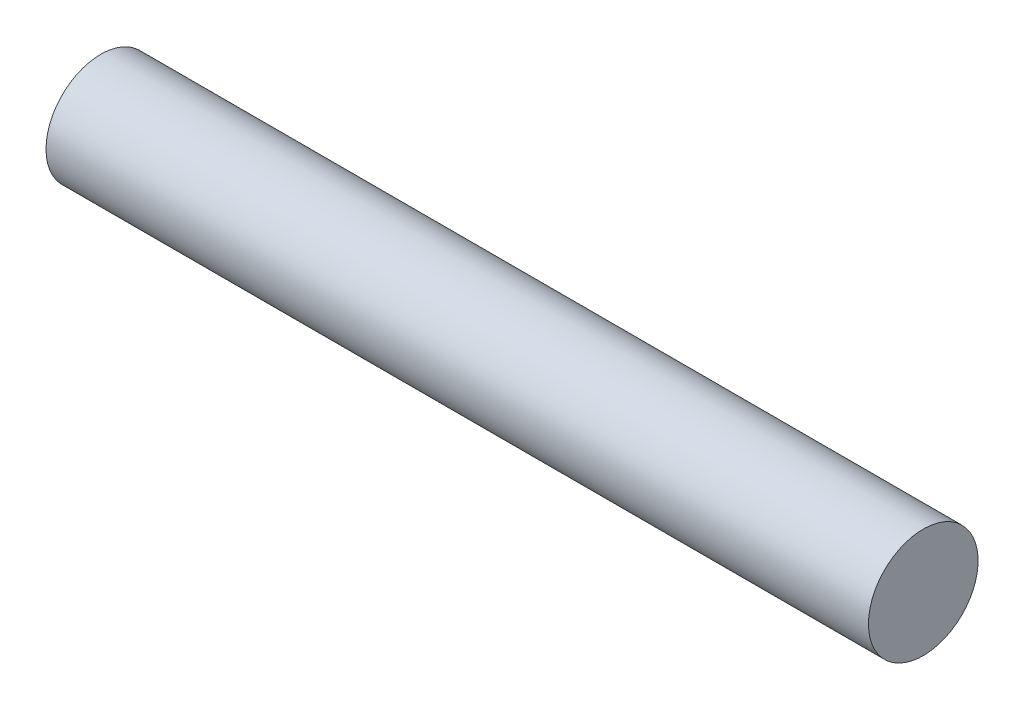
SolidWorks part; units mm, degrees
ref_plane "Ebene vorne" through (0, 0, 0) normal (0, 0, 1) x (1, 0, 0)
ref_plane "Ebene oben" through (0, 0, 0) normal (0, 1, 0) x (1, 0, 0)
ref_plane "Ebene rechts" through (0, 0, 0) normal (1, 0, 0) x (0, 0, -1)
sketch "Skizze1" plane through (0, 0, 0) normal (0, 1, 0) x (1, 0, 0)
  line L1 (-75, 5) -> (75, 5)
  line L2 (-75, 5) -> (-75, -5)
  line L3 (-75, -5) -> (75, -5)
  line L4 (75, 5) -> (75, -5)
  line L6 (-75, 0) -> (75, 0) construction
  line L7 (-22, 0) -> (22, 0) construction
  line L8 (0, 5) -> (0, -5) construction
  point P10 (0, 0)
  dimension "D1" = 10
  dimension "D2" = 150
revolve "Rotation1" add sketch "Skizze1" angle 360 about L3
